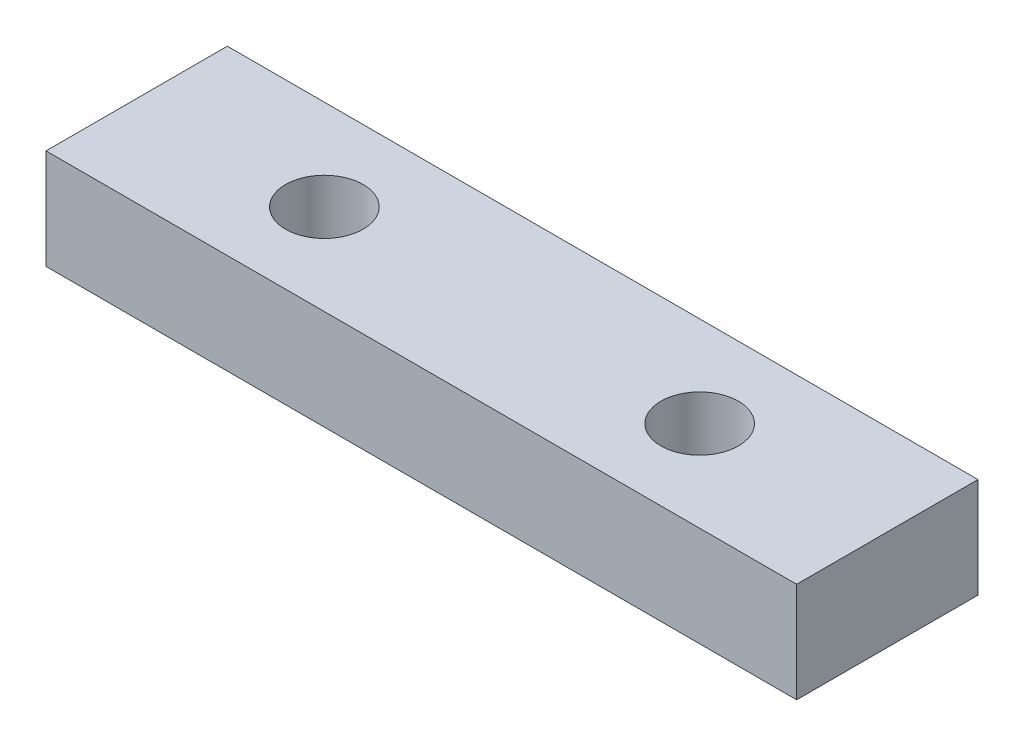
SolidWorks part; units mm, degrees
material "PLA Black"
ref_plane "Front" through (0, 0, 0) normal (0, 0, 1) x (1, 0, 0)
ref_plane "Top" through (0, 0, 0) normal (0, 1, 0) x (1, 0, 0)
ref_plane "Right" through (0, 0, 0) normal (1, 0, 0) x (0, 0, -1)
sketch "Sketch1" plane through (0, 0, 0) normal (0, 1, 0) x (1, 0, 0)
  line L0 (-13.9058, -3.6239) -> (9.3641, -3.6239) construction
  line L1 (0, 6.301) -> (0, -4.9245) construction
  line L2 (15, 0) -> (15, -7.2479) construction
  line L3 (-15, 0) -> (15, 0)
  line L4 (-15, 0) -> (-15, -7.2479)
  line L5 (-15, -7.2479) -> (15, -7.2479)
  line L6 (15, 0) -> (15, -7.2479)
  line L7 (-15, -7.2479) -> (15, -7.2479) construction
  circle A0 centre (7.5, -3.6239) radius 1.55
  circle A1 centre (-7.5, -3.6239) radius 1.55
  dimension "D3" = 3.1
  dimension "D4" = 15
extrude "Boss-Extrude1" add sketch "Sketch1" along normal blind 4 contours L3 L6 L5 L4 | A1 | A0
